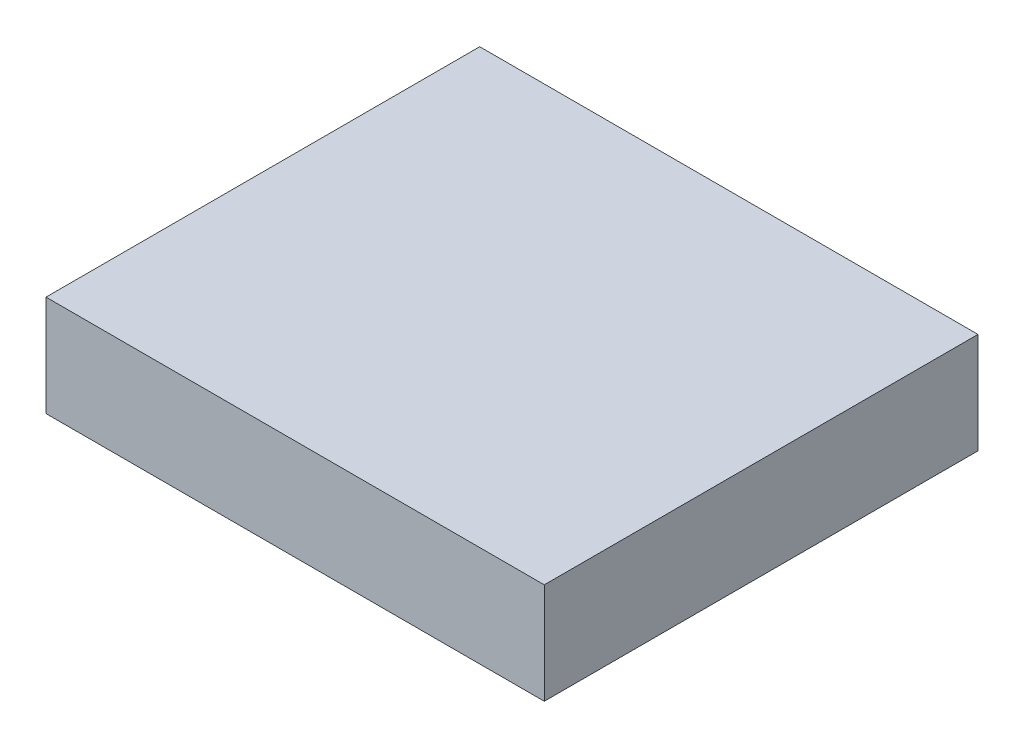
SolidWorks part; units mm, degrees
ref_plane "Front" through (0, 0, 0) normal (0, 0, 1) x (1, 0, 0)
ref_plane "Top" through (0, 0, 0) normal (0, 1, 0) x (1, 0, 0)
ref_plane "Right" through (0, 0, 0) normal (1, 0, 0) x (0, 0, -1)
sketch "草图1" plane through (0, 0, 0) normal (0, 1, 0) x (1, 0, 0)
  line L1 (0, 0) -> (24.7, 0)
  line L2 (0, 0) -> (0, -21.5)
  line L3 (0, -21.5) -> (24.7, -21.5)
  line L4 (24.7, 0) -> (24.7, -21.5)
  dimension "D1" = 24.7
  dimension "D2" = 21.5
extrude "凸台-拉伸1" add sketch "草图1" along normal blind 5
